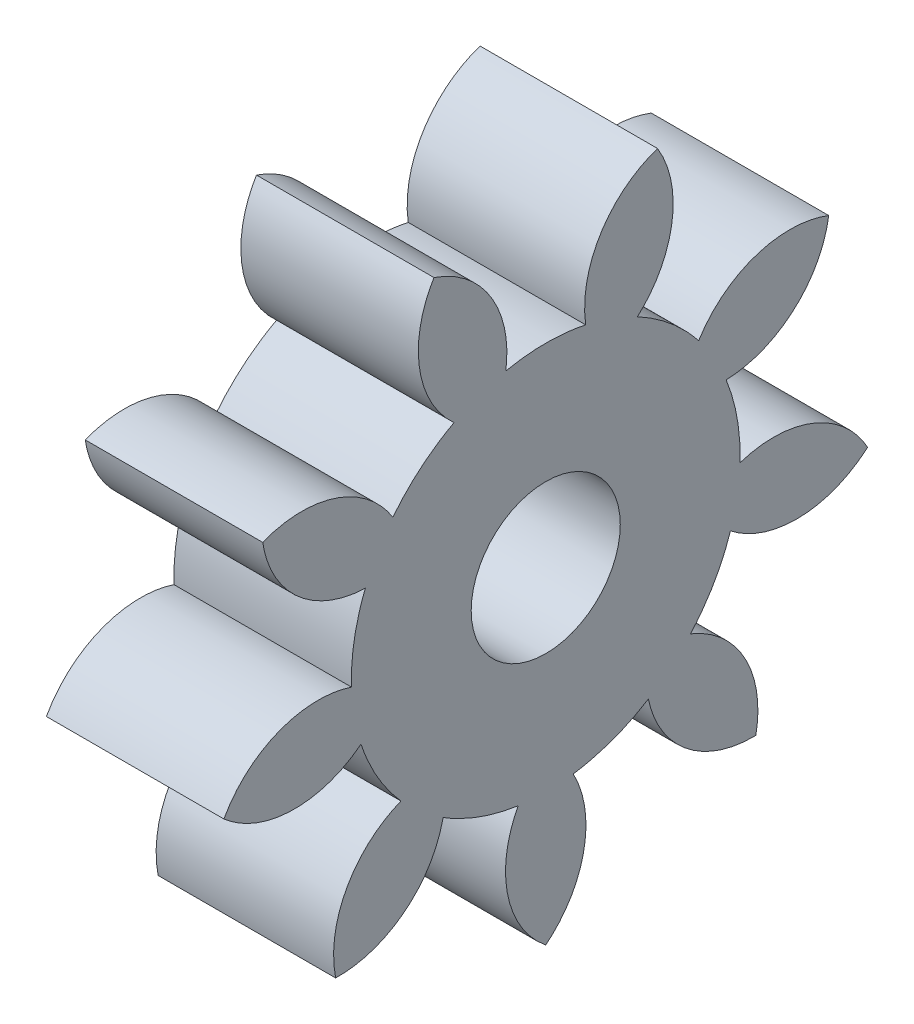
SolidWorks part; units mm, degrees
ref_plane "Plane1" through (0, 0, 0) normal (0, 0, 1) x (1, 0, 0)
ref_plane "Plane2" through (0, 0, 0) normal (0, 1, 0) x (1, 0, 0)
ref_plane "Plane3" through (0, 0, 0) normal (1, 0, 0) x (0, 0, -1)
sketch "HoldingSke" plane through (0, 0, 0) normal (0, 1, 0) x (1, 0, 0)
  line L0 (0, 0) -> (500.2823, -88.2133)
  line L1 (-15, 0) -> (100, 0) construction
  line L2 (0, 0) -> (-2.1039, 2.3779)
  line L3 (0, 0) -> (-11.863, 4.5341)
  line L4 (0, 0) -> (8.5048, 1.4996)
  line L5 (0, 0) -> (-47.5972, -17.7524)
  line L6 (0, 0) -> (-2.632, -1.7758)
  line L7 (-2.1039, 2.3779) -> (8.8308, 51.9871)
  line L8 (-76.2, 54.61) -> (-72.771, 54.61)
  line L9 (-71.009, 38.7566) -> (-53.1078, 45.2721)
  line L10 (-76.2, 71.12) -> (104.1128, 71.12)
  line L11 (0, 0) -> (-3.175, 0)
  line L12 (-76.2, 101.6) -> (-76.1492, 101.6)
  line L13 (24.9733, 27.94) -> (52.9518, 28.4284)
  line L14 (24.9733, 27.94) -> (25.0241, 27.9398)
  line L15 (24.9733, 27.94) -> (100.4021, 29.52)
  circle A0 centre (0, 0) radius 1.5875
  circle A1 centre (0, 0) radius 4.1402
  circle A2 centre (0, 0) radius 38.1
  circle A3 centre (0, 0) radius 1.5875
  dimension "MHD" = 8.2804
  dimension "Hub_dia" = 76.2
  dimension "Bore" = 3.175
  dimension "MBD" = 3.175
  dimension "Num_teeth" = 10
  dimension "Pitch_radius" = 180.3128
  dimension "Pitch" = 508
  dimension "Width" = 3.175
  dimension "Overall_len" = 50.8
  dimension "Show_teeth" = 10
  dimension "Thickness" = 3.175
  dimension "OAL" = 50.8001
  dimension "T_dim" = 3.429
  dimension "Ap" = 20
  dimension "H" = 19.05
  dimension "Backlash" = 0.0508
  dimension "Addendum_fac" = 1
  dimension "Dedendum_fac" = 1.2
  dimension "Clearance_fac" = 0.2
  dimension "Dedendum_add" = 0.0508
sketch "BasProSke" plane through (0, 0, 0) normal (0, 1, 0) x (1, 0, 0)
  line L0 (-10, 0) -> (60, 0) construction
  line L1 (0, 0) -> (0, 6.985)
  line L2 (0, 0) -> (3.175, 0)
  line L3 (3.175, 0) -> (3.175, 6.985)
  line L4 (3.175, 6.985) -> (0, 6.985)
  dimension "Diameter" = 13.97
  dimension "Thickness" = 3.175
revolve "Base-Revolve" add sketch "BasProSke" angle 360 about L0
sketch "TooCutSke" plane through (0, 0, 0) normal (1, 0, 0) x (0, 0, -1)
  line L1 (0, 0) -> (0, 107) construction
  line L2 (0, 0) -> (-1.1786, 5.5922) construction
  line L3 (0, 0) -> (-3.8703, 10.6336) construction
  line L4 (-1.1786, 5.5922) -> (-1.9352, 5.3168) construction
  arc A0 (0.8509, 4.0518) -> (-0.8509, 4.0518) centre (0, 0) ccw
  arc A1 (2.4581, 6.5653) -> (-2.4581, 6.5653) centre (0, 0) ccw
  circle A2 centre (0, 0) radius 5.715 construction
  circle A3 centre (0, 0) radius 5.3703 construction
  arc A4 (-0.8509, 4.0518) -> (-2.4581, 6.5653) centre (-3.1139, 4.3754) ccw
  arc A5 (2.4581, 6.5653) -> (0.8509, 4.0518) centre (3.1139, 4.3754) ccw
  dimension "Root_dia" = 8.2804
  dimension "Overcut_dia" = 14.0208
  dimension "Pitch_dia" = 11.43
  dimension "Base_dia" = 10.7407
  dimension "Flank_rad" = 2.286
  dimension "Half_ang" = 20
  dimension "Half_CT" = 0.8051
extrude "ToothCut" cut sketch "TooCutSke" along normal through all
fillet "Breaks" [suppressed] radius 0.0254
fillet "RootFillets" [suppressed] radius 0.3048
pattern_circular "TeethCuts" count 10 every 40 about axis through (-10, 0, 0) along (1, 0, 0) of "ToothCut"
sketch "HubNeaOneSke" plane through (0, 0, 0) normal (-1, 0, 0) x (0, 0, 1)
  circle A0 centre (0, 0) radius 4.1402
  dimension "Diameter" = 8.2804
extrude "HubNearOne" [suppressed] add sketch "HubNeaOneSke" along normal blind 47.6251
sketch "HubNeaBotSke" plane through (0, 0, 0) normal (-1, 0, 0) x (0, 0, 1)
  circle A0 centre (0, 0) radius 4.1402
  dimension "Diameter" = 8.2804
extrude "HubNearBoth" [suppressed] add sketch "HubNeaBotSke" along normal blind 23.8125
ref_plane "FarPln" through (3.175, 0, 0) normal (1, 0, 0) x (0, 0, -1)
sketch "HubFarSke" plane through (3.175, 0, 0) normal (1, 0, 0) x (0, 0, -1)
  circle A0 centre (0, 0) radius 4.1402
  dimension "Diameter" = 8.2804
extrude "HubFar" [suppressed] add sketch "HubFarSke" along normal blind 23.8125
sketch "BorSke" plane through (0, 0, 0) normal (1, 0, 0) x (0, 0, -1)
  circle A0 centre (0, 0) radius 1.5875
  dimension "Diameter" = 3.175
extrude "Bore" cut sketch "BorSke" along normal mid plane 101.6001
sketch "KeySke" plane through (0, 0, 0) normal (1, 0, 0) x (0, 0, -1)
  line L0 (-0.127, 0) -> (-0.127, 1.8415)
  line L1 (-0.127, 1.8415) -> (0.127, 1.8415)
  line L2 (0.127, 1.8415) -> (0.127, 0)
  line L3 (0, 0) -> (0, 34) construction
  line L4 (-0.127, 0) -> (0.127, 0)
  dimension "Offset" = 1.8415
  dimension "Width" = 0.254
extrude "Keyway" [suppressed] cut sketch "KeySke" along normal mid plane 101.6001
pattern_circular "Keyway2" [suppressed] count 2 every 90 about axis through (-10, 0, 0) along (1, 0, 0)
scale "Scale1" scale about centroid uniform scaling no x scale factor 1 y scale factor 0.84 z scale factor 0.84
equation "' \"Pitch@HoldingSke\" = 4"
equation "' \"Num_teeth@HoldingSke\" = 12"
equation "' \"Ap@HoldingSke\" =  20"
equation "' \"Width@HoldingSke\" = 0.5"
equation "' \"Hub_dia@HoldingSke\"= 1"
equation "' \"Overall_len@HoldingSke\" = 1.0"
equation "' \"Bore@HoldingSke\" = 0.75"
equation "' \"T_dim@HoldingSke\" = 0.85"
equation "' \"Width@KeySke\" = 0.25"
equation "' \"Show_teeth@HoldingSke\" = 13"
equation "' \"Backlash@HoldingSke\" = 0.009"
equation "' \"Addendum_fac@HoldingSke\" = 1.0"
equation "' \"Dedendum_fac@HoldingSke\" = 1.25"
equation "' \"Dedendum_add@HoldingSke\" = 0.00005"
equation "' \"Clearance_fac@HoldingSke\" = 0.25"
equation "' \"Pitch@HoldingSke\" = 0.5"
equation "' \"Num_teeth@HoldingSke\" = 23"
equation "' \"Show_teeth@HoldingSke\" = 23"
equation "' \"Backlash@HoldingSke\" = 0.0375"
equation "\"Overcut_dia@TooCutSke\"=(9 + 2 * \"Addendum_fac@HoldingSke\") / \"Pitch@HoldingSke\" + 0.002"
equation "\"Pitch_dia@TooCutSke\"=9/ \"Pitch@HoldingSke\""
equation "\"Base_dia@TooCutSke\"=9 / \"Pitch@HoldingSke\" * cos((\"Ap@HoldingSke\"  * 3.14159265 / 180))"
equation "\"Root_dia@TooCutSke\"=(9 + 2) / \"Pitch@HoldingSke\" - 2 * (\"Addendum_fac@HoldingSke\" + \"Dedendum_fac@HoldingSke\") / \"Pitch@HoldingSke\" - \"Dedendum_add@HoldingSke\" * 2"
equation "\"Half_ang@TooCutSke\"=180 / 9"
equation "\"Half_CT@TooCutSke\"=9 / \"Pitch@HoldingSke\" * sin((3.14159265 / 2 / \"Num_teeth@HoldingSke\")) / 2 - 7 * \"Backlash@HoldingSke\" / 4"
equation "\"Flank_rad@TooCutSke\"=9/ \"Pitch@HoldingSke\" / 5"
equation "\"Radius@RootFillets\" = \"Clearance_fac@HoldingSke\" / \"Pitch@HoldingSke\" + \"Dedendum_add@HoldingSke\""
equation "\"Break_rad@Breaks\" = 0.02 / \"Pitch@HoldingSke\""
equation "\"Thickness@HoldingSke\" = \"Width@HoldingSke\""
equation "\"OAL@HoldingSke\" = \"Thickness@HoldingSke\""
equation "\"MHD@HoldingSke\" = (\"Num_teeth@HoldingSke\" + 2) / \"Pitch@HoldingSke\" - 2 * (\"Addendum_fac@HoldingSke\" + \"Dedendum_fac@HoldingSke\")  / \"Pitch@HoldingSke\" - \"Dedendum_add@HoldingSke\" * 2"
equation "\"MBD@HoldingSke\" = (\"Num_teeth@HoldingSke\" + 2) / \"Pitch@HoldingSke\" - 2 * (\"Addendum_fac@HoldingSke\" + \"Dedendum_fac@HoldingSke\")  / \"Pitch@HoldingSke\" - \"Dedendum_add@HoldingSke\" * 2 - 0.002"
equation "\"MHD@HoldingSke\" = ((sgn( \"MHD@HoldingSke\" - \"Hub_dia@HoldingSke\" )-1)*( \"MHD@HoldingSke\" - \"Hub_dia@HoldingSke\" ))/-2+ \"Hub_dia@HoldingSke\""
equation "\"MBD@HoldingSke\" = ((sgn( \"MBD@HoldingSke\" - \"Bore@HoldingSke\" )-1)*( \"MBD@HoldingSke\" - \"Bore@HoldingSke\" ))/-2+ \"Bore@HoldingSke\""
equation "\"OAL@HoldingSke\" = ((sgn( \"OAL@HoldingSke\" - \"Overall_len@HoldingSke\" )+1)*( \"OAL@HoldingSke\" - \"Overall_len@HoldingSke\" ))/2 + \"Overall_len@HoldingSke\" + 0.000002"
equation "\"Num_teeth@TeethCuts\"=int( 9 ) + 1"
equation "\"Num_teeth@TeethCuts\" = ((sgn( \"Num_teeth@TeethCuts\" - \"Num_teeth@HoldingSke\" )-1)*( \"Num_teeth@TeethCuts\" - \"Num_teeth@HoldingSke\" ))/-2+ \"Num_teeth@HoldingSke\""
equation "\"Num_teeth@TeethCuts\" = ((sgn( \"Num_teeth@TeethCuts\" - 2.0)+1)*( \"Num_teeth@TeethCuts\" - 2.0))/2 +2.0"
equation "\"Angle@TeethCuts\"=360.0 / 9"
equation "\"Diameter@BasProSke\"=(9 + 2 * \"Addendum_fac@HoldingSke\") / \"Pitch@HoldingSke\""
equation "\"Thickness@BasProSke\"  = \"Thickness@HoldingSke\""
equation "' \"Fillet_rad@BasProSke\" =  \"Thickness@HoldingSke\" * 0.05"
equation "\"MHD@HoldingSke\" = ((sgn( \"MHD@HoldingSke\" - \"Root_dia@TooCutSke\" )-1)*( \"MHD@HoldingSke\" - \"Root_dia@TooCutSke\" ))/-2+ \"Root_dia@TooCutSke\""
equation "\"Diameter@HubNeaOneSke\" = \"MHD@HoldingSke\""
equation "\"Length@HubNearOne\" = \"OAL@HoldingSke\" - \"Thickness@BasProSke\""
equation "\"Diameter@HubNeaBotSke\" = \"MHD@HoldingSke\""
equation "\"Length@HubNearBoth\" = ( \"OAL@HoldingSke\" - \"Thickness@BasProSke\" ) / 2.0"
equation "\"Thickness@FarPln\" = \"Thickness@BasProSke\""
equation "\"Diameter@HubFarSke\" = \"MHD@HoldingSke\""
equation "\"Length@HubFar\" = ( \"OAL@HoldingSke\" - \"Thickness@BasProSke\" ) / 2.0"
equation "\"Diameter@BorSke\" = \"MBD@HoldingSke\""
equation "\"D1@Bore\" = \"OAL@HoldingSke\" * 2.0"
equation "\"D1@Keyway\" = \"OAL@HoldingSke\" * 2.0"
equation "\"Offset@KeySke\" = \"T_dim@HoldingSke\" - \"MBD@HoldingSke\" / 2.0"
